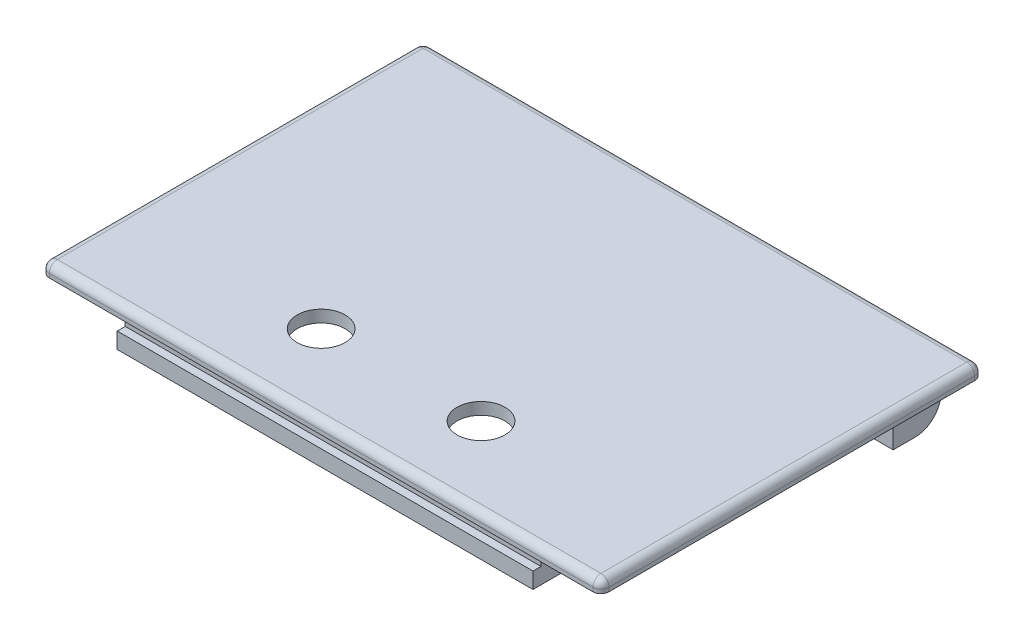
SolidWorks part; units mm, degrees
ref_plane "Piano frontale" through (0, 0, 0) normal (0, 0, 1) x (1, 0, 0)
ref_plane "Piano superiore" through (0, 0, 0) normal (0, 1, 0) x (1, 0, 0)
ref_plane "Piano destro" through (0, 0, 0) normal (1, 0, 0) x (0, 0, -1)
sketch "Schizzo1" plane through (0, 0, 0) normal (0, 1, 0) x (1, 0, 0)
  line L1 (0, 0) -> (140, 0)
  line L2 (0, 0) -> (0, 95.5)
  line L3 (0, 95.5) -> (140, 95.5)
  line L4 (140, 0) -> (140, 95.5)
  dimension "D1" = 140
  dimension "D2" = 95.5
extrude "Estrusione-Estrusione1" add sketch "Schizzo1" along normal blind 3
sketch "Schizzo2" plane through (0, 3, 0) normal (0, 1, 0) x (1, 0, 0)
  line L0 (0, 0) -> (140, 0) construction
  line L1 (0, 95.5) -> (0, 0) construction
  line L2 (140, 0) -> (140, 95.5) construction
  circle A0 centre (50, 20) radius 6
  circle A1 centre (90, 20) radius 6
  dimension "D1" = 12
  dimension "D2" = 20
  dimension "D3" = 50
  dimension "D5" = 12
  dimension "D6" = 20
  dimension "D4" = 50
extrude "Taglio-Estrusione1" cut sketch "Schizzo2" against normal up to surface (3 mm away) up to face at (70, 0, -47.75)
sketch "Schizzo3" plane through (0, 0, 0) normal (0, -1, 0) x (1, 0, 0)
  line L0 (0, 0) -> (140, 0) construction
  line L1 (18, 0) -> (122, 0)
  line L2 (18, 0) -> (18, -8)
  line L3 (18, -8) -> (122, -8)
  line L4 (122, 0) -> (122, -8)
  line L5 (140, 0) -> (140, -95.5) construction
  line L6 (0, -95.5) -> (0, 0) construction
  dimension "D1" = 18
  dimension "D2" = 18
  dimension "D3" = 8
extrude "Estrusione-Estrusione2" add sketch "Schizzo3" along normal blind 8
sketch "Schizzo4" plane through (122, 0, 0) normal (1, 0, 0) x (0, 0, -1)
  line L0 (0, 0) -> (0, -8)
  line L2 (0, 0) -> (95.5, 0) construction
  line L3 (3, 0) -> (0, 0)
  line L5 (8, -8) -> (0, -8) construction
  line L6 (1, -8) -> (0, -8)
  line L7 (1, -8) -> (1, -4)
  line L8 (1, -4) -> (3, -4)
  line L9 (3, -4) -> (3, 0)
  dimension "D1" = 3
  dimension "D2" = 1
  dimension "D3" = 4
extrude "Taglio-Estrusione2" cut sketch "Schizzo4" against normal up to surface (104 mm away) up to face at (18, -4, -4)
sketch "Schizzo5" plane through (0, 0, 0) normal (0, -1, 0) x (1, 0, 0)
  line L0 (0, -95.5) -> (0, 0) construction
  line L1 (7.2, -92.3) -> (16.2, -92.3)
  line L2 (7.2, -92.3) -> (7.2, -80.3)
  line L3 (7.2, -80.3) -> (16.2, -80.3)
  line L4 (16.2, -92.3) -> (16.2, -80.3)
  line L5 (132.8, -92.3) -> (123.8, -92.3)
  line L6 (132.8, -92.3) -> (132.8, -80.3)
  line L7 (132.8, -80.3) -> (123.8, -80.3)
  line L8 (123.8, -92.3) -> (123.8, -80.3)
  line L9 (140, 0) -> (140, -95.5) construction
  line L10 (140, -95.5) -> (0, -95.5) construction
  point P12 (11.7, -92.3)
  dimension "D1" = 9
  dimension "D2" = 9
  dimension "D3" = 7.2
  dimension "D4" = 7.2
  dimension "D5" = 12
  dimension "D6" = 12
  dimension "D7" = 3.2
  dimension "D8" = 3.2
extrude "Estrusione-Estrusione3" add sketch "Schizzo5" along normal blind 12
fillet "Raccordo1" radius 2 8 edges at (0, 1.5, -95.5) (0, 3, -47.75) (0, 1.5, 0) (70, 3, 0) (140, 1.5, 0) (140, 3, -47.75) (70, 3, -95.5) (140, 1.5, -95.5)
fillet "Raccordo2" radius 6.5 2 edges at (128.3, -12, -92.3) (11.7, -12, -92.3)
sketch "Schizzo6" plane through (7.2, 0, 0) normal (-1, 0, 0) x (0, 0, 1)
  line L0 (-93.5, 0) -> (-2, 0) construction
  line L1 (-92.3, -5.5) -> (-92.3, 0) construction
  circle A0 centre (-87.5, -5) radius 1.7
  dimension "D2" = 3.4
  dimension "D3" = 4.8
  dimension "D1" = 5
extrude "Taglio-Estrusione3" cut sketch "Schizzo6" against normal through all
sketch "Schizzo7" plane through (123.8, 0, 0) normal (-1, 0, 0) x (0, 0, 1)
  line L1 (-90.35, -6.6454) -> (-87.5, -8.2909)
  line L2 (-87.5, -8.2909) -> (-84.65, -6.6454)
  line L3 (-84.65, -6.6454) -> (-84.65, -3.3546)
  line L4 (-84.65, -3.3546) -> (-87.5, -1.7091)
  line L5 (-87.5, -1.7091) -> (-90.35, -3.3546)
  line L6 (-90.35, -3.3546) -> (-90.35, -6.6454)
  line L7 (-80.3, -12) -> (-80.3, 0) construction
  circle A0 centre (-87.5, -5) radius 2.85 construction
  dimension "D1" = 5.7
extrude "Taglio-Estrusione4" cut sketch "Schizzo7" against normal blind 2.5
sketch "Schizzo8" plane through (16.2, 0, 0) normal (1, 0, 0) x (0, 0, -1)
  line L0 (80.3, -12) -> (80.3, 0) construction
  line L1 (84.65, -6.6454) -> (87.5, -8.2909)
  line L2 (87.5, -8.2909) -> (90.35, -6.6454)
  line L3 (90.35, -6.6454) -> (90.35, -3.3546)
  line L4 (90.35, -3.3546) -> (87.5, -1.7091)
  line L5 (87.5, -1.7091) -> (84.65, -3.3546)
  line L6 (84.65, -3.3546) -> (84.65, -6.6454)
  circle A0 centre (87.5, -5) radius 2.85 construction
  circle A1 centre (87.5, -5) radius 1.7 construction
  dimension "D1" = 5.7
extrude "Taglio-Estrusione5" cut sketch "Schizzo8" against normal blind 2.5
